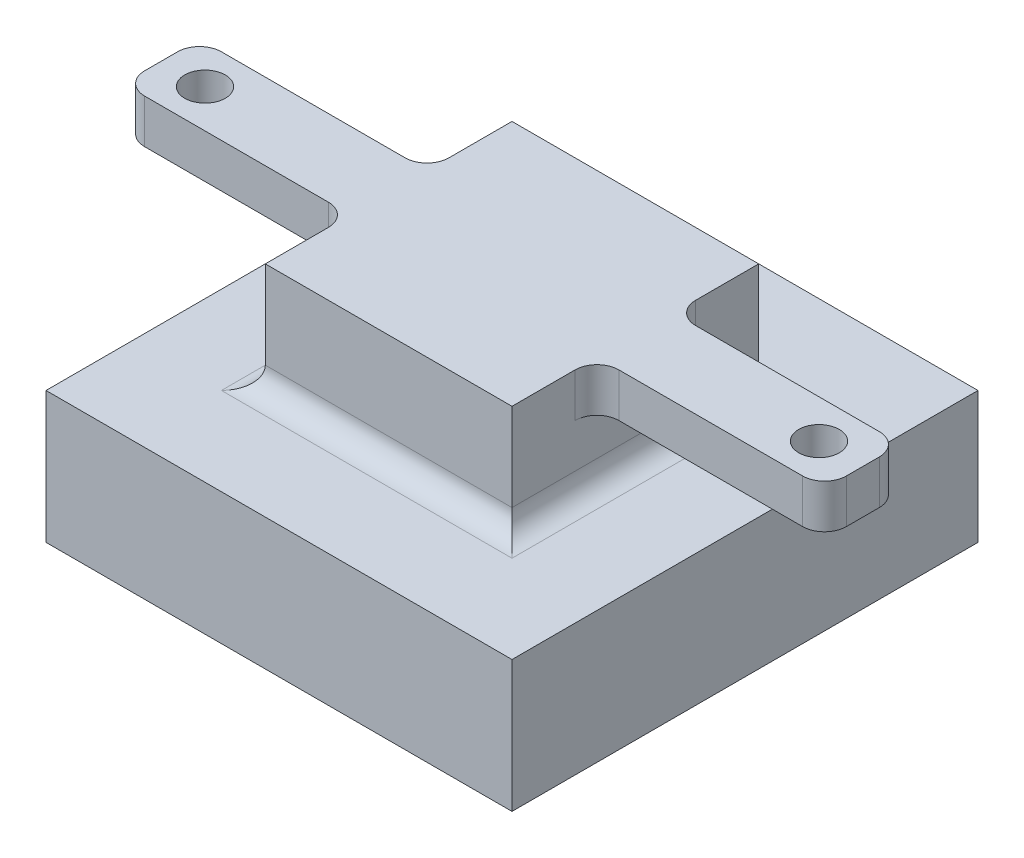
SolidWorks part; units mm, degrees
ref_plane "Front Plane" through (0, 0, 0) normal (0, 0, 1) x (1, 0, 0)
ref_plane "Top Plane" through (0, 0, 0) normal (0, 1, 0) x (1, 0, 0)
ref_plane "Right Plane" through (0, 0, 0) normal (1, 0, 0) x (0, 0, -1)
sketch "Sketch1" plane through (0, 0, 0) normal (0, 1, 0) x (1, 0, 0)
  line L0 (-21.25, -21.25) -> (-21.25, 21.25)
  line L1 (-19.25, -19.25) -> (19.25, -19.25)
  line L2 (-19.25, -19.25) -> (-19.25, 19.25)
  line L3 (-19.25, 19.25) -> (19.25, 19.25)
  line L4 (19.25, -19.25) -> (19.25, 19.25)
  line L5 (-19.25, -19.25) -> (19.25, 19.25) construction
  line L6 (-19.25, 19.25) -> (19.25, -19.25) construction
  line L7 (-21.25, 21.25) -> (21.25, 21.25)
  line L8 (21.25, -21.25) -> (21.25, 21.25)
  line L9 (-21.25, -21.25) -> (21.25, -21.25)
  point P0 (0, 0)
  dimension "D1" = 38.5
  dimension "D2" = 38.5
  dimension "D3" = 2
extrude "Boss-Extrude1" add sketch "Sketch1" along normal blind 10
sketch "Sketch2" plane through (0, 10, 0) normal (0, 1, 0) x (1, 0, 0)
  line L4 (-21.25, -21.25) -> (21.25, -21.25)
  line L5 (21.25, -21.25) -> (21.25, 21.25)
  line L6 (21.25, 21.25) -> (-21.25, 21.25)
  line L7 (-21.25, 21.25) -> (-21.25, -21.25)
  line L8 (-21.25, -21.25) -> (21.25, -21.25)
  line L9 (21.25, -21.25) -> (21.25, 21.25)
  line L10 (21.25, 21.25) -> (-21.25, 21.25)
  line L11 (-21.25, 21.25) -> (-21.25, -21.25)
  dimension "D1" = 0
extrude "Boss-Extrude2" add sketch "Sketch2" along normal blind 2
sketch "Sketch3" plane through (0, 0, 0) normal (0, -1, 0) x (1, 0, 0)
  line L0 (19.25, -19.25) -> (-19.25, -19.25) construction
  line L1 (19.25, -19.25) -> (-19.25, -19.25)
  line L2 (0, 0) -> (0, -21.25) construction
  line L3 (4, -19.25) -> (4, -21.25)
  line L4 (21.25, 21.25) -> (-21.25, 21.25)
  line L5 (-21.25, 21.25) -> (-21.25, -21.25)
  line L6 (-21.25, -21.25) -> (21.25, -21.25)
  line L7 (21.25, -21.25) -> (21.25, 21.25)
  line L8 (21.25, 21.25) -> (-21.25, 21.25)
  line L9 (-21.25, 21.25) -> (-21.25, -21.25)
  line L10 (-21.25, -21.25) -> (21.25, -21.25)
  line L11 (21.25, -21.25) -> (21.25, 21.25)
  line L12 (-4, -19.25) -> (-4, -21.25)
  line M9 (-21.25, -21.25) -> (21.25, -21.25)
  line M12 (19.25, -19.25) -> (-19.25, -19.25)
  dimension "D2" = 4
  dimension "D1" = 0
extrude "Cut-Extrude1" cut sketch "Sketch3" against normal up to surface (10 mm away) contours L2 L12 L10 M12 | L1 L2 L3 M9 up to face at (0, 10, 0)
sketch "Sketch5" plane through (0, 12, 0) normal (0, 1, 0) x (1, 0, 0)
  line L0 (-11.25, 11.25) -> (-11.25, -11.25)
  line L1 (-11.25, -11.25) -> (11.25, -11.25)
  line L2 (11.25, -11.25) -> (11.25, 11.25)
  line L3 (11.25, 11.25) -> (-11.25, 11.25)
  line L4 (-21.25, 21.25) -> (-21.25, -21.25)
  line L5 (-21.25, -21.25) -> (21.25, -21.25)
  line L6 (21.25, -21.25) -> (21.25, 21.25)
  line L7 (21.25, 21.25) -> (-21.25, 21.25)
  line L8 (-21.25, 21.25) -> (-21.25, -21.25)
  line L9 (-21.25, -21.25) -> (21.25, -21.25)
  line L10 (21.25, -21.25) -> (21.25, 21.25)
  line L11 (21.25, 21.25) -> (-21.25, 21.25)
  dimension "D1" = 0
  dimension "D2" = 10
extrude "Boss-Extrude3" add sketch "Sketch5" along normal blind 10 contours L0 L1 L2 L3
sketch "Sketch6" plane through (0, 22, 0) normal (0, 1, 0) x (1, 0, 0)
  line L0 (0, 0) -> (32, 0) construction
  line L1 (11.25, 3.5) -> (32, 3.5)
  line L2 (11.25, -11.25) -> (11.25, 11.25) construction
  line L3 (32, 3.5) -> (32, -3.5)
  line L4 (11.25, -3.5) -> (32, -3.5)
  circle A0 centre (28, 0) radius 1.85
  line M7 (11.25, -11.25) -> (11.25, 11.25)
  dimension "D3" = 3.7
  dimension "D1" = 32
  dimension "D2" = 28
  dimension "D4" = 7
extrude "Boss-Extrude4" add sketch "Sketch6" against normal blind 4 contours L0 L4 L3 A0 M7 | L0 A0 L3 L1 M7
mirror "Mirror2" about plane through (0, 0, 0) normal (1, 0, 0) of "Boss-Extrude4"
fillet "Fillet1" radius 2 12 edges at (-11.25, 20, -3.5) (-11.25, 20, 3.5) (11.25, 20, -3.5) (11.25, 20, 3.5) (11.25, 12, 0) (0, 12, -11.25) (0, 12, 11.25) (-11.25, 12, 0) (-32, 20, 3.5) (-32, 20, -3.5) (32, 20, 3.5) (32, 20, -3.5)
fillet "Fillet2" radius 3 2 edges at (4, 0, -20.25) (-4, 0, -20.25)
